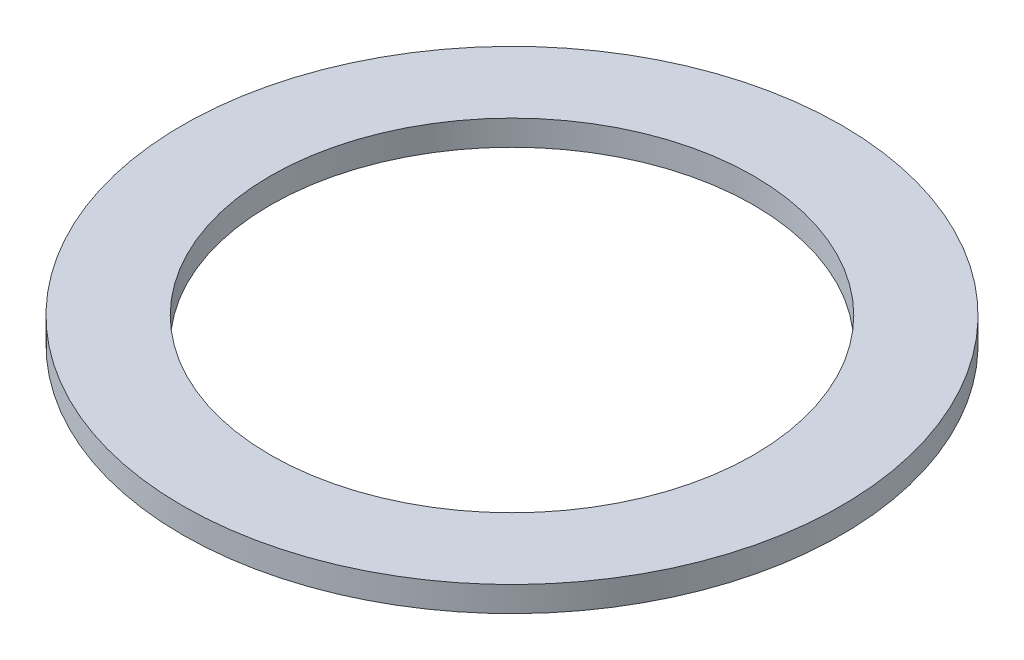
SolidWorks part; units mm, degrees
ref_plane "Front Plane" through (0, 0, 0) normal (0, 0, 1) x (1, 0, 0)
ref_plane "Top Plane" through (0, 0, 0) normal (0, 1, 0) x (1, 0, 0)
ref_plane "Right Plane" through (0, 0, 0) normal (1, 0, 0) x (0, 0, -1)
sketch "Sketch2" plane through (0, 0, 0) normal (0, 1, 0) x (1, 0, 0)
  circle A0 centre (0, 0) radius 27.5
  circle A1 centre (0, 0) radius 37.5
  dimension "D1" = 55
  dimension "D2" = 75
extrude "Boss-Extrude1" add sketch "Sketch2" along normal blind 2.87
